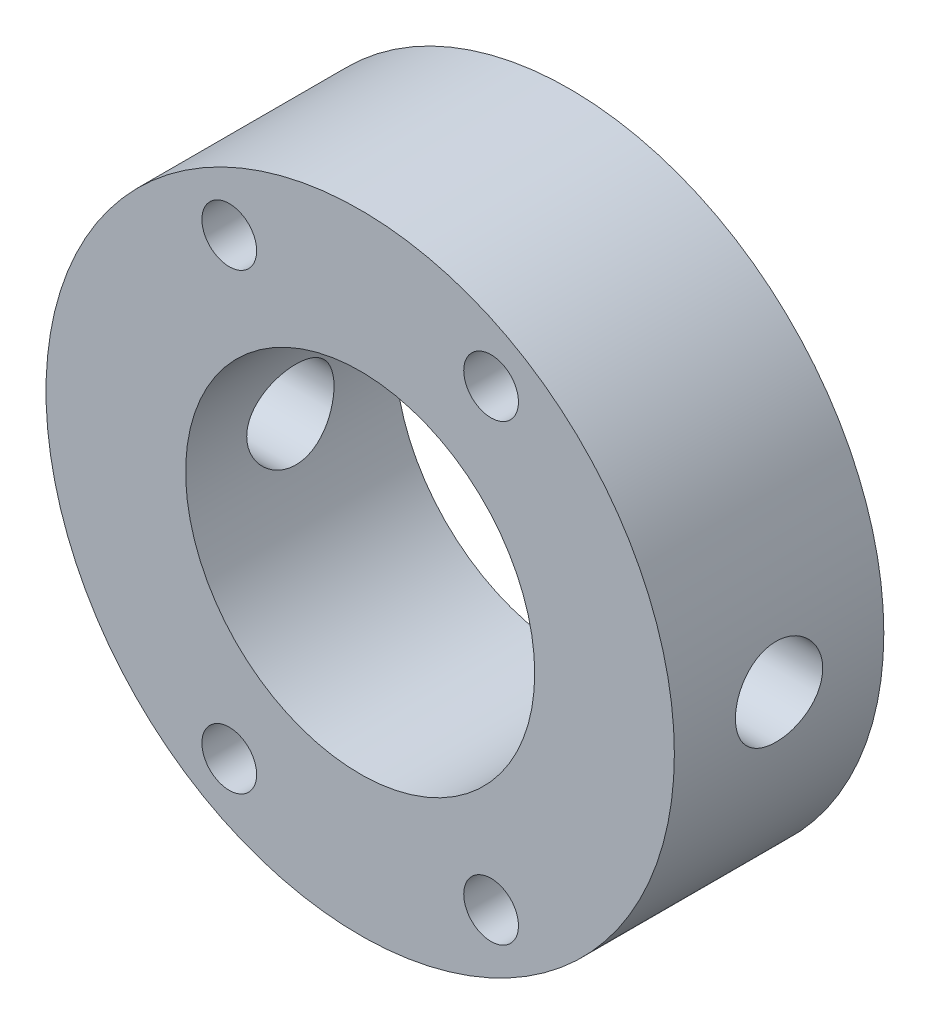
SolidWorks part; units mm, degrees
ref_plane "Front Plane" through (0, 0, 0) normal (0, 0, 1) x (1, 0, 0)
ref_plane "Top Plane" through (0, 0, 0) normal (0, 1, 0) x (1, 0, 0)
ref_plane "Right Plane" through (0, 0, 0) normal (1, 0, 0) x (0, 0, -1)
sketch "Sketch1" plane through (0, 0, 0) normal (0, 0, 1) x (1, 0, 0)
  line L0 (-28.575, 0) -> (28.575, 0) construction
  line L1 (0, -28.575) -> (0, 28.575) construction
  circle A0 centre (0, 0) radius 28.575
  circle A1 centre (0, 0) radius 15.875
  point P4 (0, 0)
  point P9 (0, 0)
  point P10 (15.875, 0)
  dimension "D1" = 31.75
  dimension "OD" = 57.15
  dimension "Wall Thickness" = 12.7
sketch "Sketch2" plane through (0, 0, 0) normal (1, 0, 0) x (0, 0, -1)
  line L0 (76.2, 28.575) -> (-76.2, 28.575) construction
  line L1 (0, 28.575) -> (0, -28.575) construction
  point P3 (-47.625, 28.575)
  point P4 (0, 28.575)
  point P5 (47.625, 28.575)
  dimension "D1" = 28.575
  dimension "D2" = 28.575
  dimension "Length" = 152.4
sketch "Sketch3" plane through (0, 0, 0) normal (0, 0, 1) x (1, 0, 0)
  line L0 (0, -28.575) -> (0, 28.575) construction
  circle A0 centre (0, 0) radius 28.575
  circle A1 centre (0, 0) radius 15.875
  circle A2 centre (0, 0) radius 15.875 construction
extrude "Boss-Extrude1" add sketch "Sketch3" along normal mid plane 152.4
sketch "Sketch4" plane through (0, 0, -76.2) normal (0, 0, -1) x (-1, 0, 0)
  circle A0 centre (0, 0) radius 39.559
extrude "Cut-Extrude1" cut sketch "Sketch4" against normal offset from surface (133.35 mm away) 19.05 up to face at (28.575, 0, 76.2)
sketch "Sketch5" plane through (0, 0, 57.15) normal (0, 0, -1) x (-1, 0, 0)
  circle A0 centre (0, 0) radius 23.8125 construction
  point P3 (-11.9063, 20.6222)
  point P4 (11.9063, 20.6222)
  point P5 (0, 0)
  point P6 (-12.8218, -20.0658)
  point P7 (11.9063, -20.6222)
  point P8 (-11.9063, -20.6222)
  point P9 (0, 0)
  dimension "D1" = 47.625
  dimension "D2" = 60
  dimension "D3" = 2
hole_wizard "#9 (0.196) Diameter Hole1" positions "Sketch5" profile "Sketch6" hole size "#9" standard "ANSI Inch" end condition through all
sketch "Sketch6" plane through (11.9063, -20.6222, 57.15) normal (1, 0, 0) x (0, 1, 0)
  line L0 (0, 0) -> (0, 19.05)
  line L1 (0, 19.05) -> (2.4892, 19.05)
  line L2 (2.4892, 19.05) -> (2.4892, 0)
  line L5 (2.4892, 0) -> (0, 0)
  line L11 (0, -6.35) -> (0, 107.95) construction
  dimension "Thru Hole Dia." = 4.9784
  dimension "Thru Hole Depth" = 19.05
sketch "Sketch7" plane through (0, 0, 0) normal (1, 0, 0) x (0, 0, -1)
  line L0 (-76.2, 0) -> (-66.675, 0) construction
  line L1 (-76.2, 28.575) -> (-76.2, -28.575) construction
  line L2 (-66.675, 0) -> (-57.15, 0) construction
  line L3 (-57.15, -28.575) -> (-57.15, 28.575) construction
  circle A0 centre (-66.675, 0) radius 3.9687
  point P0 (-66.675, 0)
  point P1 (-89.255, 5.9982)
  dimension "D1" = 7.9375
extrude "Cut-Extrude2" cut sketch "Sketch7" against normal through all both and the other way through all contours A0
equation "\"D1@Boss-Extrude1\" = \"Length@Sketch2\""
equation "\"D1@Sketch2\"=\"OD@Sketch1\"*.5"
equation "\"D2@Sketch2\"=\"D1@Sketch2\""
